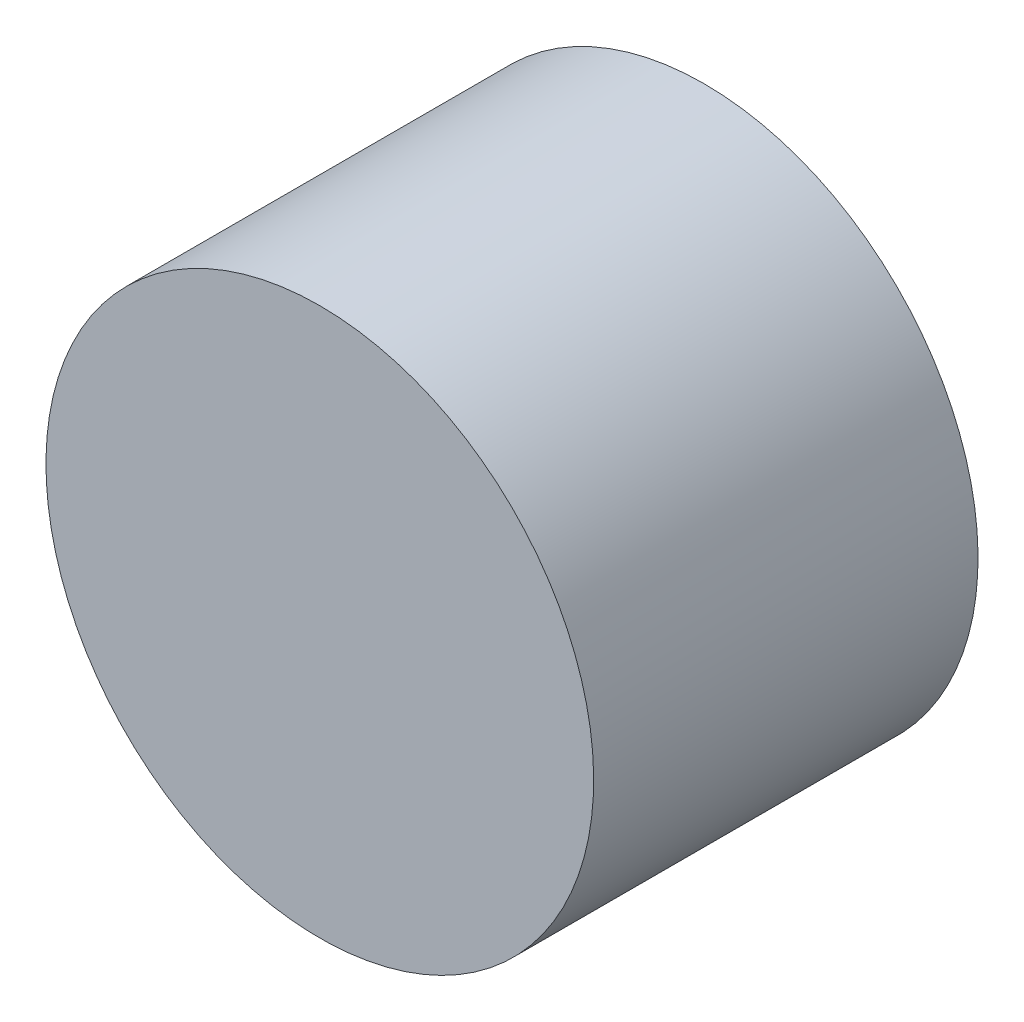
SolidWorks part; units mm, degrees
ref_plane "Plan de face" through (0, 0, 0) normal (0, 0, 1) x (1, 0, 0)
ref_plane "Plan de dessus" through (0, 0, 0) normal (0, 1, 0) x (1, 0, 0)
ref_plane "Plan de droite" through (0, 0, 0) normal (1, 0, 0) x (0, 0, -1)
sketch "Esquisse1" plane through (0, 0, 0) normal (1, 0, 0) x (0, 0, -1)
  line L0 (18.9402, 0) -> (-43.742, 0) construction
  line L1 (-40, 0) -> (-40, 28.5)
  line L2 (-40, 28.5) -> (0, 28.5)
  line L3 (0, 28.5) -> (0, 13.5)
  line L4 (0, 13.5) -> (-28, 13.5)
  line L5 (-28, 13.5) -> (-28, 0)
  line L6 (-28, 0) -> (-40, 0)
  dimension "D1" = 40
  dimension "D2" = 28
  dimension "D3" = 27
  dimension "D4" = 57
revolve "Révolution1" add sketch "Esquisse1" angle 360 about L6
